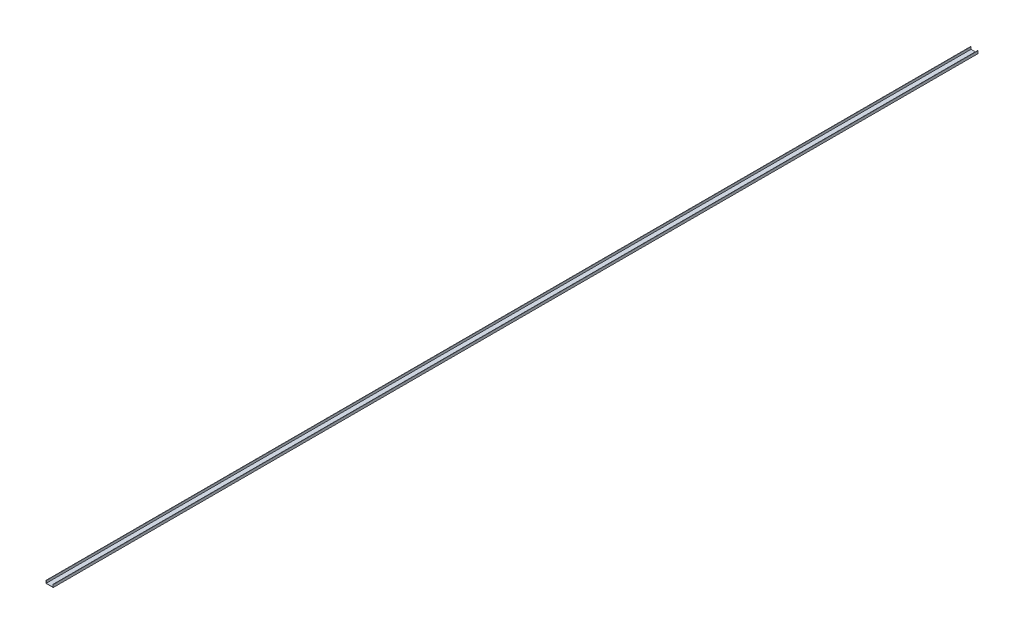
SolidWorks part; units mm, degrees
material "2014 合金"
ref_plane "前视基准面" through (0, 0, 0) normal (0, 0, 1) x (1, 0, 0)
ref_plane "上视基准面" through (0, 0, 0) normal (0, 1, 0) x (1, 0, 0)
ref_plane "右视基准面" through (0, 0, 0) normal (1, 0, 0) x (0, 0, -1)
other "Configuration Table"
sketch "草图1" plane through (0, 0, 0) normal (0, 0, 1) x (1, 0, 0)
  line L0 (0, 10) -> (0, 0)
  line L1 (0, 0) -> (27, 0)
  line L2 (27, 0) -> (27, 10)
  line L3 (27, 10) -> (26, 10)
  line L4 (26, 10) -> (26, 1)
  line L5 (26, 1) -> (1, 1)
  line L6 (1, 1) -> (1, 10)
  line L7 (1, 10) -> (0, 10)
  dimension "D1" = 27
  dimension "D2" = 10
  dimension "D3" = 10
  dimension "D4" = 1
  dimension "D5" = 1
  dimension "D6" = 1
extrude "凸台-拉伸1" add sketch "草图1" along normal blind 3460
